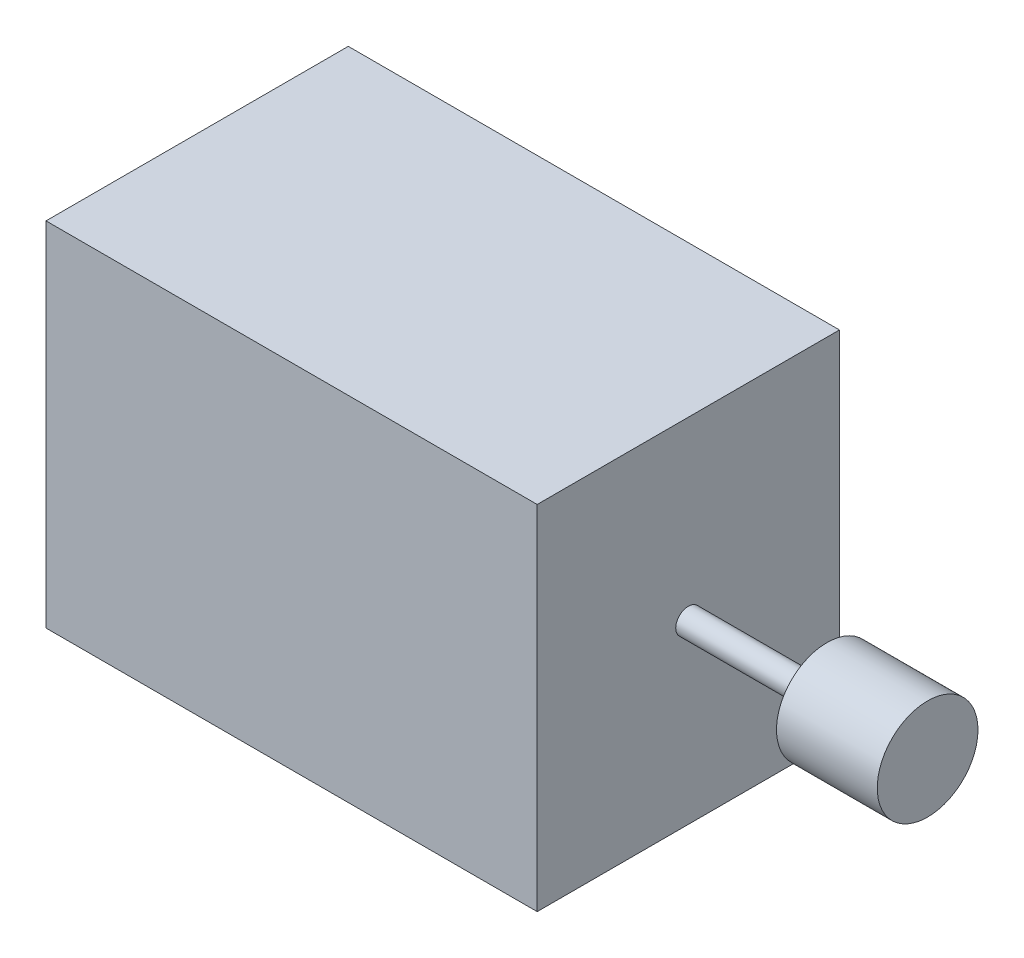
SolidWorks part; units mm, degrees
ref_plane "Front Plane" through (0, 0, 0) normal (0, 0, 1) x (1, 0, 0)
ref_plane "Top Plane" through (0, 0, 0) normal (0, 1, 0) x (1, 0, 0)
ref_plane "Right Plane" through (0, 0, 0) normal (1, 0, 0) x (0, 0, -1)
sketch "Sketch2" plane through (0, 0, 0) normal (0, 1, 0) x (1, 0, 0)
  line L1 (-19.5, -12) -> (19.5, -12)
  line L2 (-19.5, -12) -> (-19.5, 12)
  line L3 (-19.5, 12) -> (19.5, 12)
  line L4 (19.5, -12) -> (19.5, 12)
  line L5 (-19.5, -12) -> (19.5, 12) construction
  line L6 (-19.5, 12) -> (19.5, -12) construction
  point P0 (0, 0)
  dimension "D1" = 24
  dimension "D2" = 39
extrude "Boss-Extrude1" add sketch "Sketch2" along normal mid plane 28
sketch "Sketch3" plane through (19.5, 0, 0) normal (1, 0, 0) x (0, 0, -1)
  circle A0 centre (0, 0) radius 1
  dimension "D1" = 2
extrude "Boss-Extrude2" add sketch "Sketch3" along normal blind 11
sketch "Sketch4" plane through (30.5, 0, 0) normal (1, 0, 0) x (0, 0, -1)
  circle A0 centre (0, 0) radius 4
  dimension "D1" = 8
extrude "Boss-Extrude3" add sketch "Sketch4" along normal blind 8
sketch "Sketch5" plane through (0, -14, 0) normal (0, 1, 0) x (1, 0, 0)
  line L4 (-19.5, -12) -> (19.5, -12) construction
  line L5 (19.5, 12) -> (-19.5, 12) construction
  line L6 (-19.5, 12) -> (-19.5, -12) construction
  line L7 (19.5, -12) -> (19.5, 12) construction
  circle A0 centre (-9.5, 10.5) radius 1.4
  circle A1 centre (-9.5, -10.5) radius 1.4
  circle A2 centre (9.5, 10.5) radius 1.4
  circle A3 centre (9.5, -10.5) radius 1.4
  dimension "D1" = 1.5
  dimension "D2" = 1.5
  dimension "D3" = 10
  dimension "D4" = 10
  dimension "D5" = 2.8
extrude "Cut-Extrude3" cut sketch "Sketch5" along normal blind 8
